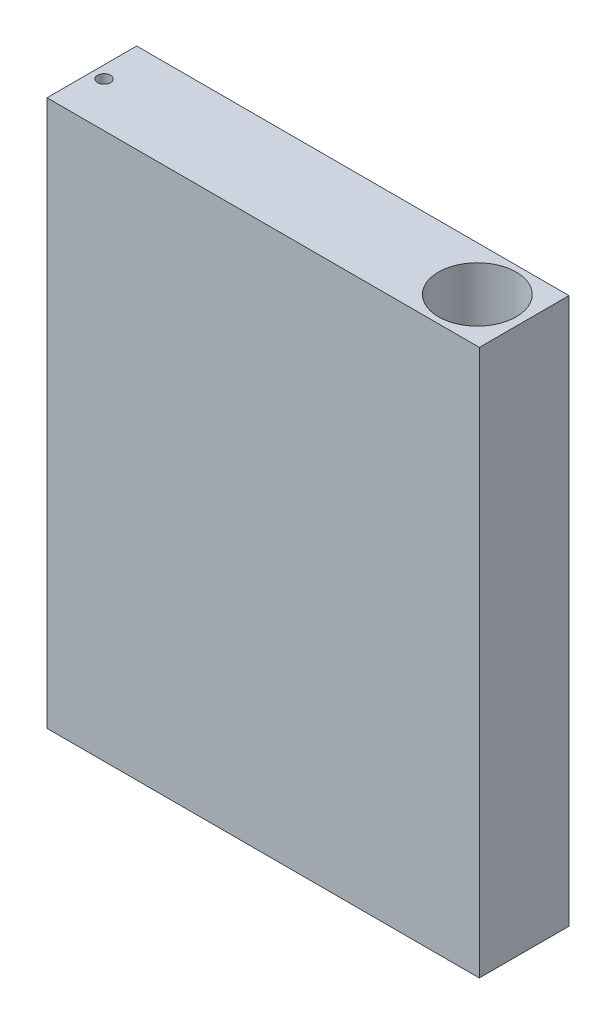
SolidWorks part; units mm, degrees
ref_plane "Front Plane" through (0, 0, 0) normal (0, 0, 1) x (1, 0, 0)
ref_plane "Top Plane" through (0, 0, 0) normal (0, 1, 0) x (1, 0, 0)
ref_plane "Right Plane" through (0, 0, 0) normal (1, 0, 0) x (0, 0, -1)
sketch "Sketch2" plane through (0, 0, 0) normal (0, 1, 0) x (1, 0, 0)
  line L1 (0, 0) -> (53.04, 0)
  line L2 (0, 0) -> (0, 11)
  line L3 (0, 11) -> (53.04, 11)
  line L4 (53.04, 0) -> (53.04, 11)
  dimension "D1" = 53.04
  dimension "D2" = 11
extrude "Boss-Extrude1" add sketch "Sketch2" along normal blind 67
sketch "Sketch3" plane through (0, 67, 0) normal (0, 1, 0) x (1, 0, 0)
  line L1 (53.04, 11) -> (0, 11) construction
  line L2 (53.04, 0) -> (53.04, 11) construction
  circle A0 centre (47.29, 5.5) radius 4.765
  dimension "D1" = 9.53
  dimension "D2" = 5.5
  dimension "D3" = 5.75
extrude "Cut-Extrude1" cut sketch "Sketch3" against normal through all
sketch "Sketch4" plane through (0, 67, 0) normal (0, 1, 0) x (1, 0, 0)
  line L0 (53.04, 11) -> (0, 11) construction
  line L1 (0, 11) -> (0, 0) construction
  circle A0 centre (1.5, 5.5) radius 0.795
  dimension "D3" = 1.59
  dimension "D1" = 5.5
  dimension "D2" = 1.5
extrude "Cut-Extrude2" cut sketch "Sketch4" against normal blind 33.5
